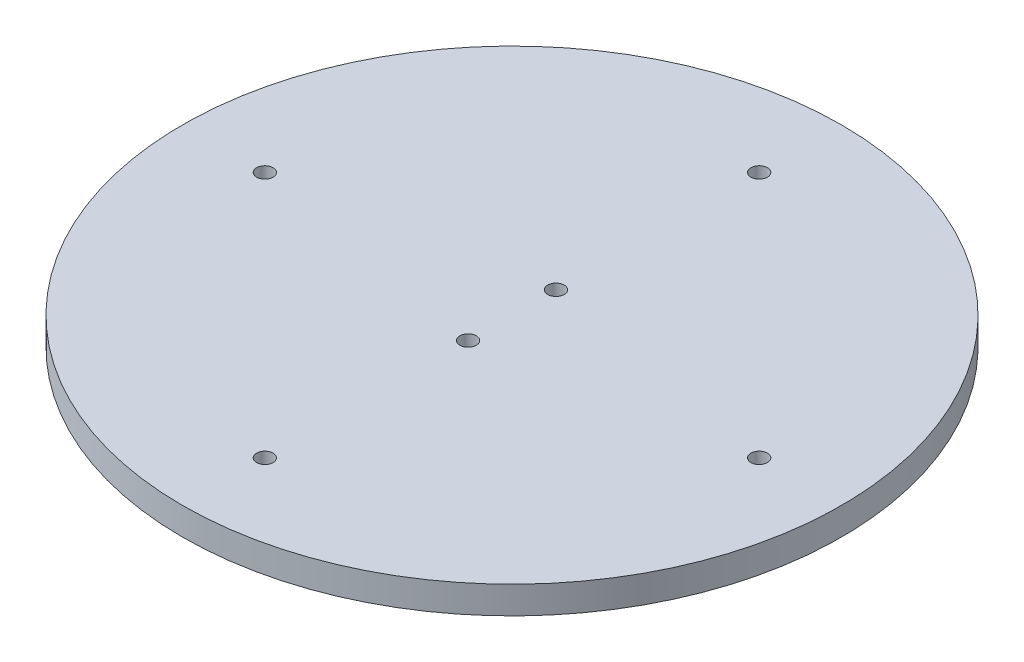
SolidWorks part; units mm, degrees
material "Acrylic (Medium-high impact)"
ref_plane "Front Plane" through (0, 0, 0) normal (0, 0, 1) x (1, 0, 0)
ref_plane "Top Plane" through (0, 0, 0) normal (0, 1, 0) x (1, 0, 0)
ref_plane "Right Plane" through (0, 0, 0) normal (1, 0, 0) x (0, 0, -1)
sketch "Sketch1" plane through (0, 0, 0) normal (0, 1, 0) x (1, 0, 0)
  circle A0 centre (0, 0) radius 60
  point P14 (0, 0)
  dimension "D1" = 120
extrude "Boss-Extrude1" add sketch "Sketch1" along normal blind 5 contours A0
sketch "Sketch2" plane through (0, 5, 0) normal (0, 1, 0) x (1, 0, 0)
  circle A0 centre (45, 0) radius 1.5
  circle A1 centre (0, -45) radius 1.5
  circle A2 centre (-45, 0) radius 1.5
  circle A3 centre (0, 45) radius 1.5
  point P12 (0, 0)
  dimension "D3" = 3
  dimension "D1" = 45
  dimension "D2" = 4
extrude "Cut-Extrude1" cut sketch "Sketch2" against normal blind 5
sketch "Sketch3" plane through (0, 5, 0) normal (0, 1, 0) x (1, 0, 0)
  line L0 (0, 0) -> (10.1993, 0) construction
  circle A0 centre (0, -8) radius 1.5
  circle A1 centre (0, 8) radius 1.5
  dimension "D1" = 3
  dimension "D2" = 8
extrude "Cut-Extrude2" cut sketch "Sketch3" against normal up to next
